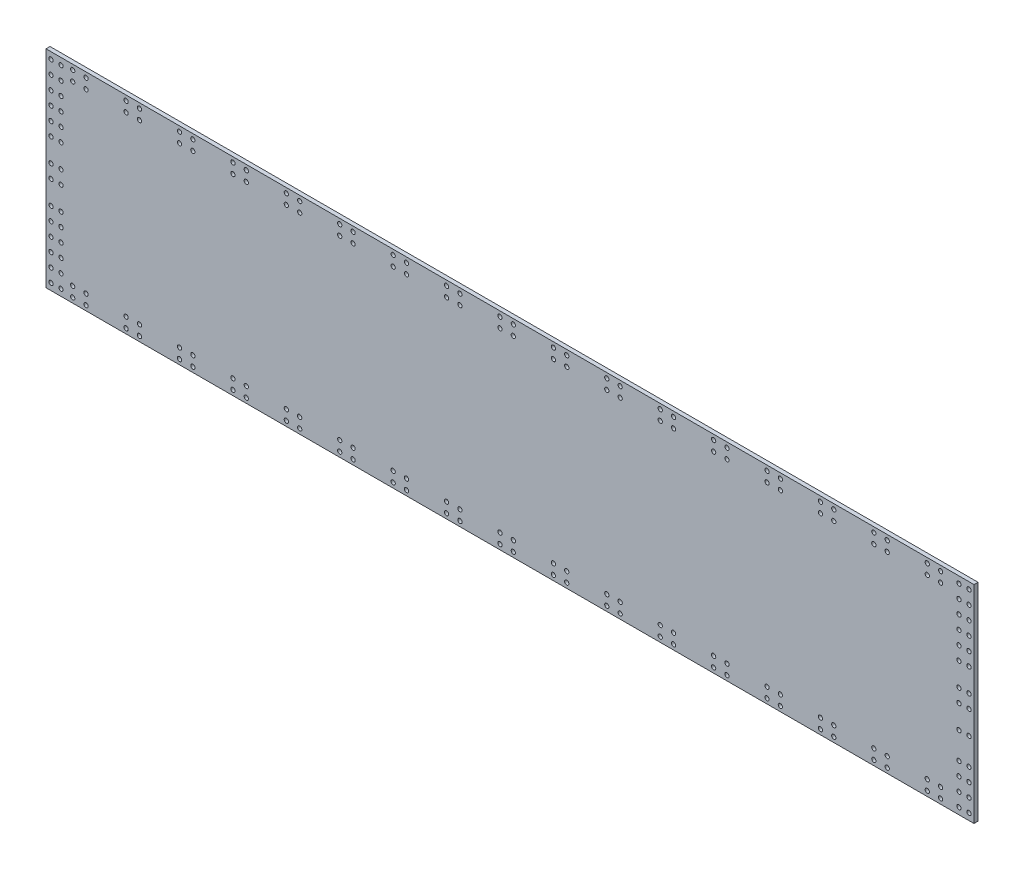
SolidWorks part; units mm, degrees
ref_plane "前视基准面" through (0, 0, 0) normal (0, 0, 1) x (1, 0, 0)
ref_plane "上视基准面" through (0, 0, 0) normal (0, 1, 0) x (1, 0, 0)
ref_plane "右视基准面" through (0, 0, 0) normal (1, 0, 0) x (0, 0, -1)
other "Configuration Table"
sketch "草图1" plane through (0, 0, 0) normal (0, 0, 1) x (1, 0, 0)
  line L1 (0, 0) -> (695, 0)
  line L2 (0, 0) -> (0, -155)
  line L3 (0, -155) -> (695, -155)
  line L4 (695, 0) -> (695, -155)
  dimension "D1" = 695
  dimension "D2" = 155
extrude "凸台-拉伸1" add sketch "草图1" along normal blind 3
sketch "草图2" plane through (0, 0, 3) normal (0, 0, 1) x (1, 0, 0)
  line L0 (0, -145) -> (695, -145) construction
  line L1 (0, 0) -> (0, -155) construction
  line L2 (695, -155) -> (695, 0) construction
  line L3 (0, -147.5) -> (695, -147.5) construction
  line L4 (0, -77.5) -> (695, -77.5) construction
  line L5 (0, -155) -> (695, -155) construction
  line L6 (25, -147.5) -> (25, -155) construction
  line L7 (7.5, -155) -> (7.5, 0) construction
  line L8 (695, 0) -> (0, 0) construction
  line L9 (7.5, -125) -> (0, -125) construction
  line L10 (7.5, -30) -> (0, -30) construction
  line L11 (25, -7.5) -> (25, 0) construction
  line L12 (347.5, 0) -> (347.5, -155) construction
  line L13 (25, -7.5) -> (25, 0) construction
  line L14 (687.5, -30) -> (695, -30) construction
  line L15 (687.5, -125) -> (695, -125) construction
  line L16 (687.5, -155) -> (687.5, 0) construction
  line L18 (0, -40) -> (7.5, -40) construction
  line L19 (7.5, -50) -> (0, -50) construction
  line L20 (7.5, -105) -> (0, -105) construction
  line L21 (687.5, -105) -> (695, -105) construction
  line L22 (687.5, -50) -> (695, -50) construction
  circle A0 centre (20, -151.25) radius 1.6
  circle A1 centre (20, -143.75) radius 1.6
  circle A2 centre (30, -151.25) radius 1.6
  circle A3 centre (30, -143.75) radius 1.6
  circle A4 centre (3.75, -130) radius 1.6
  circle A5 centre (3.75, -120) radius 1.6
  circle A6 centre (11.25, -130) radius 1.6
  circle A7 centre (11.25, -120) radius 1.6
  circle A8 centre (11.25, -35) radius 1.6
  circle A9 centre (11.25, -25) radius 1.6
  circle A10 centre (3.75, -35) radius 1.6
  circle A11 centre (3.75, -25) radius 1.6
  circle A12 centre (30, -11.25) radius 1.6
  circle A13 centre (30, -3.75) radius 1.6
  circle A14 centre (20, -11.25) radius 1.6
  circle A15 centre (20, -3.75) radius 1.6
  circle A20 centre (691.25, -25) radius 1.6
  circle A21 centre (691.25, -35) radius 1.6
  circle A22 centre (683.75, -25) radius 1.6
  circle A23 centre (683.75, -35) radius 1.6
  circle A24 centre (683.75, -120) radius 1.6
  circle A25 centre (683.75, -130) radius 1.6
  circle A26 centre (691.25, -120) radius 1.6
  circle A27 centre (691.25, -130) radius 1.6
  circle A32 centre (3.75, -55) radius 1.6
  circle A33 centre (3.75, -45) radius 1.6
  circle A34 centre (11.25, -55) radius 1.6
  circle A35 centre (11.25, -45) radius 1.6
  circle A36 centre (11.25, -110) radius 1.6
  circle A37 centre (11.25, -100) radius 1.6
  circle A38 centre (3.75, -110) radius 1.6
  circle A39 centre (3.75, -100) radius 1.6
  circle A40 centre (691.25, -100) radius 1.6
  circle A41 centre (683.75, -100) radius 1.6
  circle A42 centre (683.75, -45) radius 1.6
  circle A43 centre (683.75, -55) radius 1.6
  circle A44 centre (691.25, -45) radius 1.6
  circle A45 centre (691.25, -55) radius 1.6
  circle A46 centre (3.75, -72.5) radius 1.6
  circle A47 centre (11.25, -72.5) radius 1.6
  circle A48 centre (11.25, -82.5) radius 1.6
  circle A49 centre (3.75, -82.5) radius 1.6
  circle A50 centre (691.25, -82.5) radius 1.6
  circle A51 centre (683.75, -82.5) radius 1.6
  circle A52 centre (683.75, -72.5) radius 1.6
  circle A53 centre (691.25, -72.5) radius 1.6
  circle A54 centre (60, -143.75) radius 1.6
  circle A55 centre (70, -143.75) radius 1.6
  circle A56 centre (60, -151.25) radius 1.6
  circle A57 centre (70, -151.25) radius 1.6
  circle A58 centre (100, -143.75) radius 1.6
  circle A59 centre (110, -143.75) radius 1.6
  circle A60 centre (100, -151.25) radius 1.6
  circle A61 centre (110, -151.25) radius 1.6
  circle A62 centre (140, -143.75) radius 1.6
  circle A63 centre (150, -143.75) radius 1.6
  circle A64 centre (140, -151.25) radius 1.6
  circle A65 centre (150, -151.25) radius 1.6
  circle A66 centre (180, -143.75) radius 1.6
  circle A67 centre (190, -143.75) radius 1.6
  circle A68 centre (180, -151.25) radius 1.6
  circle A69 centre (190, -151.25) radius 1.6
  circle A70 centre (220, -143.75) radius 1.6
  circle A71 centre (230, -143.75) radius 1.6
  circle A72 centre (220, -151.25) radius 1.6
  circle A73 centre (230, -151.25) radius 1.6
  circle A74 centre (260, -143.75) radius 1.6
  circle A75 centre (270, -143.75) radius 1.6
  circle A76 centre (260, -151.25) radius 1.6
  circle A77 centre (270, -151.25) radius 1.6
  circle A78 centre (300, -143.75) radius 1.6
  circle A79 centre (310, -143.75) radius 1.6
  circle A80 centre (300, -151.25) radius 1.6
  circle A81 centre (310, -151.25) radius 1.6
  circle A82 centre (340, -143.75) radius 1.6
  circle A83 centre (350, -143.75) radius 1.6
  circle A84 centre (340, -151.25) radius 1.6
  circle A85 centre (350, -151.25) radius 1.6
  circle A86 centre (380, -143.75) radius 1.6
  circle A87 centre (390, -143.75) radius 1.6
  circle A88 centre (380, -151.25) radius 1.6
  circle A89 centre (390, -151.25) radius 1.6
  circle A90 centre (420, -143.75) radius 1.6
  circle A91 centre (430, -143.75) radius 1.6
  circle A92 centre (420, -151.25) radius 1.6
  circle A93 centre (430, -151.25) radius 1.6
  circle A94 centre (460, -143.75) radius 1.6
  circle A95 centre (470, -143.75) radius 1.6
  circle A96 centre (460, -151.25) radius 1.6
  circle A97 centre (470, -151.25) radius 1.6
  circle A98 centre (500, -143.75) radius 1.6
  circle A99 centre (510, -143.75) radius 1.6
  circle A100 centre (500, -151.25) radius 1.6
  circle A101 centre (510, -151.25) radius 1.6
  circle A102 centre (540, -143.75) radius 1.6
  circle A103 centre (550, -143.75) radius 1.6
  circle A104 centre (540, -151.25) radius 1.6
  circle A105 centre (550, -151.25) radius 1.6
  circle A106 centre (580, -143.75) radius 1.6
  circle A107 centre (590, -143.75) radius 1.6
  circle A108 centre (580, -151.25) radius 1.6
  circle A109 centre (590, -151.25) radius 1.6
  circle A110 centre (620, -143.75) radius 1.6
  circle A111 centre (630, -143.75) radius 1.6
  circle A112 centre (620, -151.25) radius 1.6
  circle A113 centre (630, -151.25) radius 1.6
  circle A114 centre (660, -143.75) radius 1.6
  circle A115 centre (670, -143.75) radius 1.6
  circle A116 centre (660, -151.25) radius 1.6
  circle A117 centre (670, -151.25) radius 1.6
  circle A118 centre (30, -11.25) radius 1.6
  circle A119 centre (30, -3.75) radius 1.6
  circle A120 centre (20, -11.25) radius 1.6
  circle A121 centre (20, -3.75) radius 1.6
  circle A122 centre (60, -3.75) radius 1.6
  circle A123 centre (70, -3.75) radius 1.6
  circle A124 centre (60, -11.25) radius 1.6
  circle A125 centre (70, -11.25) radius 1.6
  circle A126 centre (100, -3.75) radius 1.6
  circle A127 centre (110, -3.75) radius 1.6
  circle A128 centre (100, -11.25) radius 1.6
  circle A129 centre (110, -11.25) radius 1.6
  circle A130 centre (140, -3.75) radius 1.6
  circle A131 centre (150, -3.75) radius 1.6
  circle A132 centre (140, -11.25) radius 1.6
  circle A133 centre (150, -11.25) radius 1.6
  circle A134 centre (180, -3.75) radius 1.6
  circle A135 centre (190, -3.75) radius 1.6
  circle A136 centre (180, -11.25) radius 1.6
  circle A137 centre (190, -11.25) radius 1.6
  circle A138 centre (220, -3.75) radius 1.6
  circle A139 centre (230, -3.75) radius 1.6
  circle A140 centre (220, -11.25) radius 1.6
  circle A141 centre (230, -11.25) radius 1.6
  circle A142 centre (260, -3.75) radius 1.6
  circle A143 centre (270, -3.75) radius 1.6
  circle A144 centre (260, -11.25) radius 1.6
  circle A145 centre (270, -11.25) radius 1.6
  circle A146 centre (300, -3.75) radius 1.6
  circle A147 centre (310, -3.75) radius 1.6
  circle A148 centre (300, -11.25) radius 1.6
  circle A149 centre (310, -11.25) radius 1.6
  circle A150 centre (340, -3.75) radius 1.6
  circle A151 centre (350, -3.75) radius 1.6
  circle A152 centre (340, -11.25) radius 1.6
  circle A153 centre (350, -11.25) radius 1.6
  circle A154 centre (380, -3.75) radius 1.6
  circle A155 centre (390, -3.75) radius 1.6
  circle A156 centre (380, -11.25) radius 1.6
  circle A157 centre (390, -11.25) radius 1.6
  circle A158 centre (420, -3.75) radius 1.6
  circle A159 centre (430, -3.75) radius 1.6
  circle A160 centre (420, -11.25) radius 1.6
  circle A161 centre (430, -11.25) radius 1.6
  circle A162 centre (460, -3.75) radius 1.6
  circle A163 centre (470, -3.75) radius 1.6
  circle A164 centre (460, -11.25) radius 1.6
  circle A165 centre (470, -11.25) radius 1.6
  circle A166 centre (500, -3.75) radius 1.6
  circle A167 centre (510, -3.75) radius 1.6
  circle A168 centre (500, -11.25) radius 1.6
  circle A169 centre (510, -11.25) radius 1.6
  circle A170 centre (540, -3.75) radius 1.6
  circle A171 centre (550, -3.75) radius 1.6
  circle A172 centre (540, -11.25) radius 1.6
  circle A173 centre (550, -11.25) radius 1.6
  circle A174 centre (580, -3.75) radius 1.6
  circle A175 centre (590, -3.75) radius 1.6
  circle A176 centre (580, -11.25) radius 1.6
  circle A177 centre (590, -11.25) radius 1.6
  circle A178 centre (620, -3.75) radius 1.6
  circle A179 centre (630, -3.75) radius 1.6
  circle A180 centre (620, -11.25) radius 1.6
  circle A181 centre (630, -11.25) radius 1.6
  circle A182 centre (660, -3.75) radius 1.6
  circle A183 centre (670, -3.75) radius 1.6
  circle A184 centre (660, -11.25) radius 1.6
  circle A185 centre (670, -11.25) radius 1.6
  circle A186 centre (3.75, -150) radius 1.6
  circle A187 centre (3.75, -140) radius 1.6
  circle A188 centre (11.25, -150) radius 1.6
  circle A189 centre (11.25, -140) radius 1.6
  circle A190 centre (11.25, -15) radius 1.6
  circle A191 centre (11.25, -5) radius 1.6
  circle A192 centre (3.75, -15) radius 1.6
  circle A193 centre (3.75, -5) radius 1.6
  circle A194 centre (683.75, -140) radius 1.6
  circle A195 centre (683.75, -150) radius 1.6
  circle A196 centre (691.25, -140) radius 1.6
  circle A197 centre (691.25, -150) radius 1.6
  circle A198 centre (691.25, -5) radius 1.6
  circle A199 centre (691.25, -15) radius 1.6
  circle A200 centre (683.75, -5) radius 1.6
  circle A201 centre (683.75, -15) radius 1.6
  dimension "D3" = 3.2
  dimension "D8" = 3.2
  dimension "D13" = 3.2
  dimension "D20" = 3.2
  dimension "D1" = 7.5
  dimension "D2" = 10
  dimension "D4" = 3.75
  dimension "D5" = 25
  dimension "D6" = 5
  dimension "D7" = 7.5
  dimension "D9" = 3.75
  dimension "D10" = 25
  dimension "D11" = 5
  dimension "D12" = 10
  dimension "D14" = 3.75
  dimension "D15" = 5
  dimension "D17" = 40
  dimension "D19" = 40
  dimension "D21" = 3.75
  dimension "D22" = 5
  dimension "D16" = 17
  dimension "D18" = 17
extrude "切除-拉伸1" cut sketch "草图2" against normal blind 3
